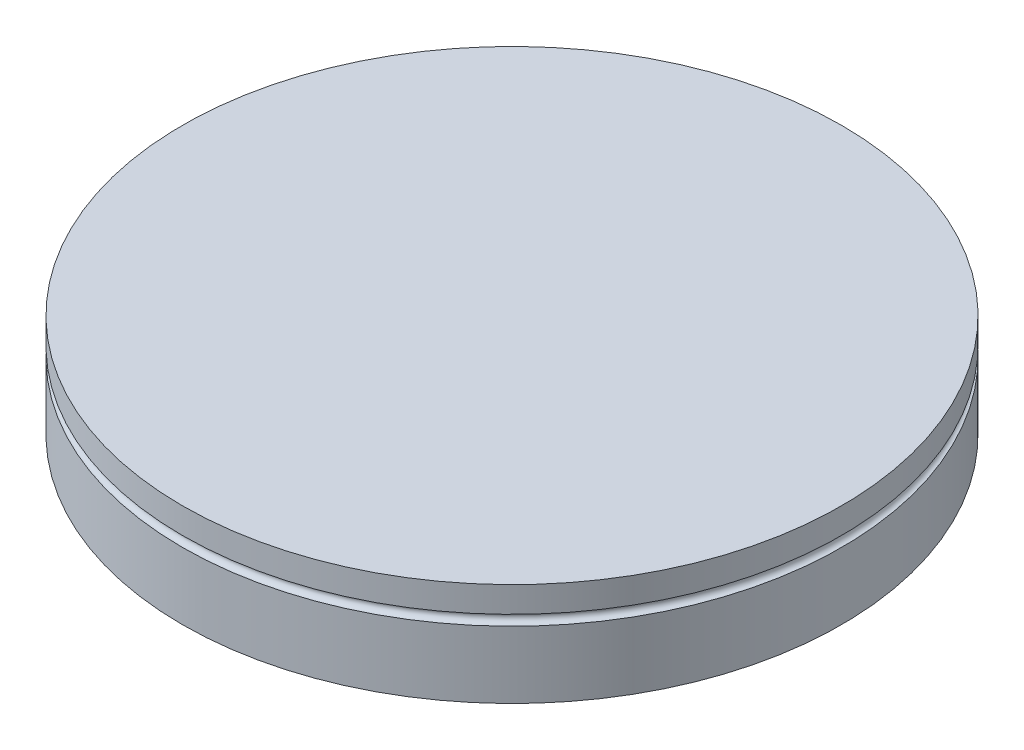
SolidWorks part; units mm, degrees
ref_plane "Płaszczyzna przednia" through (0, 0, 0) normal (0, 0, 1) x (1, 0, 0)
ref_plane "Płaszczyzna górna" through (0, 0, 0) normal (0, 1, 0) x (1, 0, 0)
ref_plane "Płaszczyzna prawa" through (0, 0, 0) normal (1, 0, 0) x (0, 0, -1)
sketch "Szkic1" plane through (0, 0, 0) normal (0, 1, 0) x (1, 0, 0)
  circle A0 centre (0, 0) radius 64
  dimension "D1" = 128
extrude "Dodanie-wyciągnięcie1" add sketch "Szkic1" along normal blind 20
sketch "Szkic3" plane through (0, 0, 0) normal (0, 0, 1) x (1, 0, 0)
  line L0 (64, 0) -> (-64, 0)
  line L1 (-64, 0) -> (-64, 20)
  line L2 (-64, 20) -> (64, 20)
  line L3 (64, 20) -> (64, 0)
  line L4 (0, 20) -> (0, 0) construction
  circle A0 centre (64, 14) radius 1
  circle A1 centre (-64, 14) radius 1
  dimension "D1" = 6
  dimension "D2" = 6
revolve "Wycięcie-obrót1" cut sketch "Szkic3" angle 360 about L4
